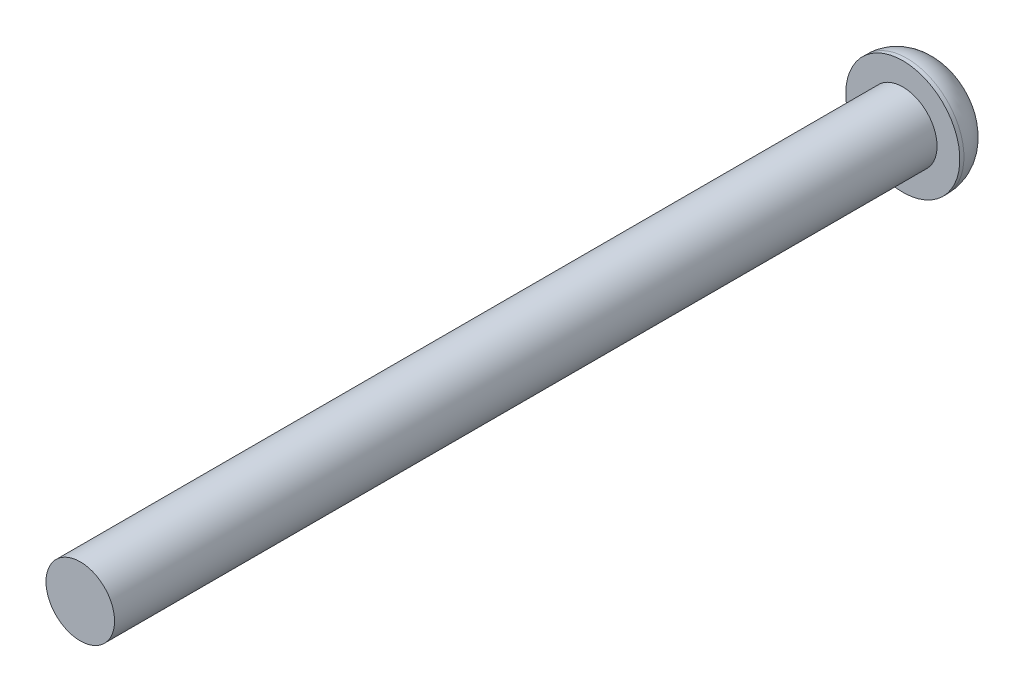
SolidWorks part; units mm, degrees
ref_plane "Front Plane" through (0, 0, 0) normal (0, 0, 1) x (1, 0, 0)
ref_plane "Top Plane" through (0, 0, 0) normal (0, 1, 0) x (1, 0, 0)
ref_plane "Right Plane" through (0, 0, 0) normal (1, 0, 0) x (0, 0, -1)
sketch "Sketch1" plane through (0, 0, 0) normal (0, 0, 1) x (1, 0, 0)
  circle A0 centre (0, 0) radius 2.5
  dimension "D1" = 5
extrude "Boss-Extrude1" add sketch "Sketch1" along normal blind 60
sketch "Sketch2" plane through (0, 0, 0) normal (0, 0, -1) x (-1, 0, 0)
  circle A0 centre (0, 0) radius 4.1596
extrude "Boss-Extrude2" add sketch "Sketch2" along normal blind 2.8
fillet "Fillet1" radius 2.5 1 edges at (-4.1596, 0, -2.8)
sketch "Sketch3" plane through (0, 0, -2.8) normal (0, 0, -1) x (-1, 0, 0)
  line L1 (1.3924, -0.6365) -> (1.2475, 0.8876)
  line L2 (1.2475, 0.8876) -> (-0.145, 1.5241)
  line L3 (-0.145, 1.5241) -> (-1.3924, 0.6365)
  line L4 (-1.3924, 0.6365) -> (-1.2475, -0.8876)
  line L5 (-1.2475, -0.8876) -> (0.145, -1.5241)
  line L6 (0.145, -1.5241) -> (1.3924, -0.6365)
  circle A0 centre (0, 0) radius 1.3259 construction
extrude "Cut-Extrude1" cut sketch "Sketch3" against normal blind 2
